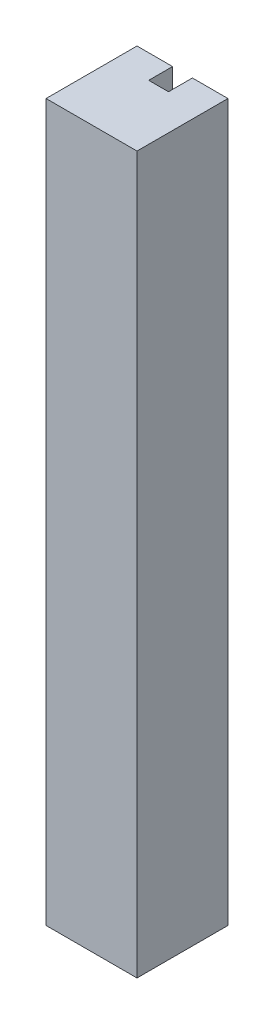
SolidWorks part; units mm, degrees
ref_plane "Front Plane" through (0, 0, 0) normal (0, 0, 1) x (1, 0, 0)
ref_plane "Top Plane" through (0, 0, 0) normal (0, 1, 0) x (1, 0, 0)
ref_plane "Right Plane" through (0, 0, 0) normal (1, 0, 0) x (0, 0, -1)
sketch "Esquisse1" plane through (0, 0, 0) normal (0, 1, 0) x (1, 0, 0)
  line L0 (0, 0) -> (0, 38.1)
  line L1 (0, 38.1) -> (14.9, 38.1)
  line L2 (14.9, 38.1) -> (14.9, 28.1)
  line L3 (14.9, 28.1) -> (23.2, 28.1)
  line L4 (23.2, 28.1) -> (23.2, 38.1)
  line L5 (23.2, 38.1) -> (38.1, 38.1)
  line L6 (38.1, 38.1) -> (38.1, 0)
  line L7 (38.1, 0) -> (0, 0)
  dimension "D1" = 38.1
  dimension "D2" = 38.1
  dimension "D3" = 8.3
  dimension "D4" = 10
extrude "Boss.-Extru.1" add sketch "Esquisse1" along normal blind 300
